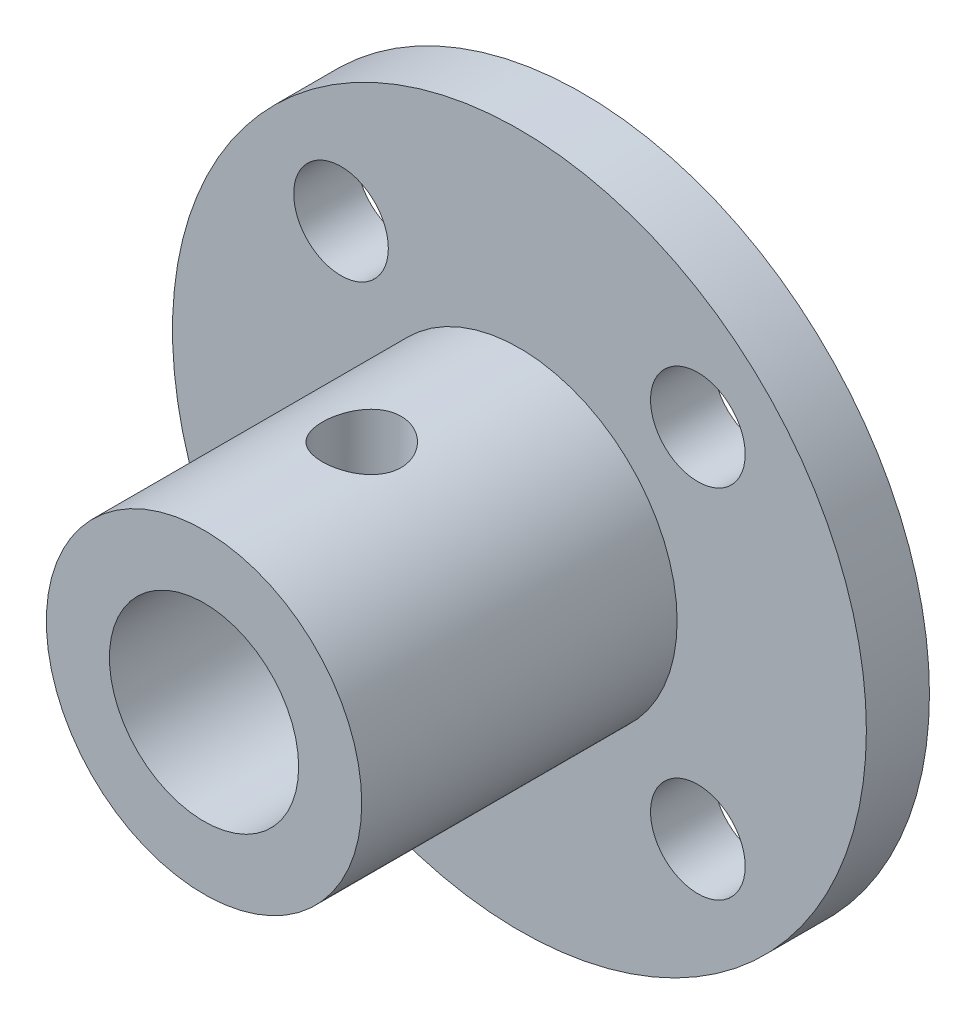
SolidWorks part; units mm, degrees
material "Plain Carbon Steel"
ref_plane "Front Plane" through (0, 0, 0) normal (0, 0, 1) x (1, 0, 0)
ref_plane "Top Plane" through (0, 0, 0) normal (0, 1, 0) x (1, 0, 0)
ref_plane "Right Plane" through (0, 0, 0) normal (1, 0, 0) x (0, 0, -1)
sketch "Sketch1" plane through (0, 0, 0) normal (0, 0, 1) x (1, 0, 0)
  circle A0 centre (0, 0) radius 11
  dimension "D1" = 22
extrude "Boss-Extrude1" add sketch "Sketch1" along normal blind 2 contours A0
sketch "Sketch2" plane through (0, 0, 2) normal (0, 0, 1) x (1, 0, 0)
  circle A0 centre (0, 0) radius 5
  dimension "D1" = 10
extrude "Boss-Extrude2" add sketch "Sketch2" along normal blind 10
sketch "Sketch3" plane through (0, 0, 12) normal (0, 0, 1) x (1, 0, 0)
  circle A0 centre (0, 0) radius 3
  dimension "D1" = 6
extrude "Cut-Extrude1" cut sketch "Sketch3" against normal up to next
hole_wizard "Tap Drill for M3x0.5 Tap1" positions "Sketch4" profile "Sketch5" hole size "M3x0.5" standard "ANSI Metric"
sketch "Sketch4" plane through (0, 0, 0) normal (0, 1, 0) x (1, 0, 0)
  line L0 (-5, -2) -> (-5, -12) construction
  line L1 (-5, -2) -> (-5, -12) construction
  point P0 (0, -7)
  point P5 (-5, -7)
sketch "Sketch5" plane through (0, 0, 7) normal (1, 0, 0) x (0, 0, -1)
  line L0 (0, 0) -> (0, 5)
  line L1 (0, 5) -> (1.25, 5)
  line L2 (1.25, 5) -> (1.25, 0)
  line L5 (1.25, 0) -> (0, 0)
  line L11 (0, -6.35) -> (0, 107.95) construction
  dimension "Thru Hole Dia." = 2.5
  dimension "Thru Hole Depth" = 5
hole_wizard "Ø3.0mm Dowel Hole1" positions "Sketch6" profile "Sketch7" hole size "Ø3.0" standard "ANSI Metric" end condition up to next
sketch "Sketch6" plane through (0, 0, 2) normal (0, 0, 1) x (1, 0, 0)
  line L1 (-5.6569, -5.6569) -> (5.6569, -5.6569) construction
  line L2 (-5.6569, -5.6569) -> (-5.6569, 5.6569) construction
  line L3 (-5.6569, 5.6569) -> (5.6569, 5.6569) construction
  line L4 (5.6569, -5.6569) -> (5.6569, 5.6569) construction
  line L5 (-5.6569, -5.6569) -> (5.6569, 5.6569) construction
  line L6 (-5.6569, 5.6569) -> (5.6569, -5.6569) construction
  point P2 (5.6569, 5.6569)
  point P59 (-5.6569, -5.6569)
  point P60 (-5.6569, 5.6569)
  point P61 (5.6569, -5.6569)
  dimension "D1" = 16
sketch "Sketch7" plane through (5.6569, 5.6569, 2) normal (1, 0, 0) x (0, -1, 0)
  line L0 (0, 0) -> (0, 2)
  line L1 (0, 2) -> (1.5, 2)
  line L2 (1.5, 2) -> (1.5, 0)
  line L5 (1.5, 0) -> (0, 0)
  line L11 (0, -6.35) -> (0, 107.95) construction
  dimension "Thru Hole Dia." = 3
  dimension "Thru Hole Depth" = 2
